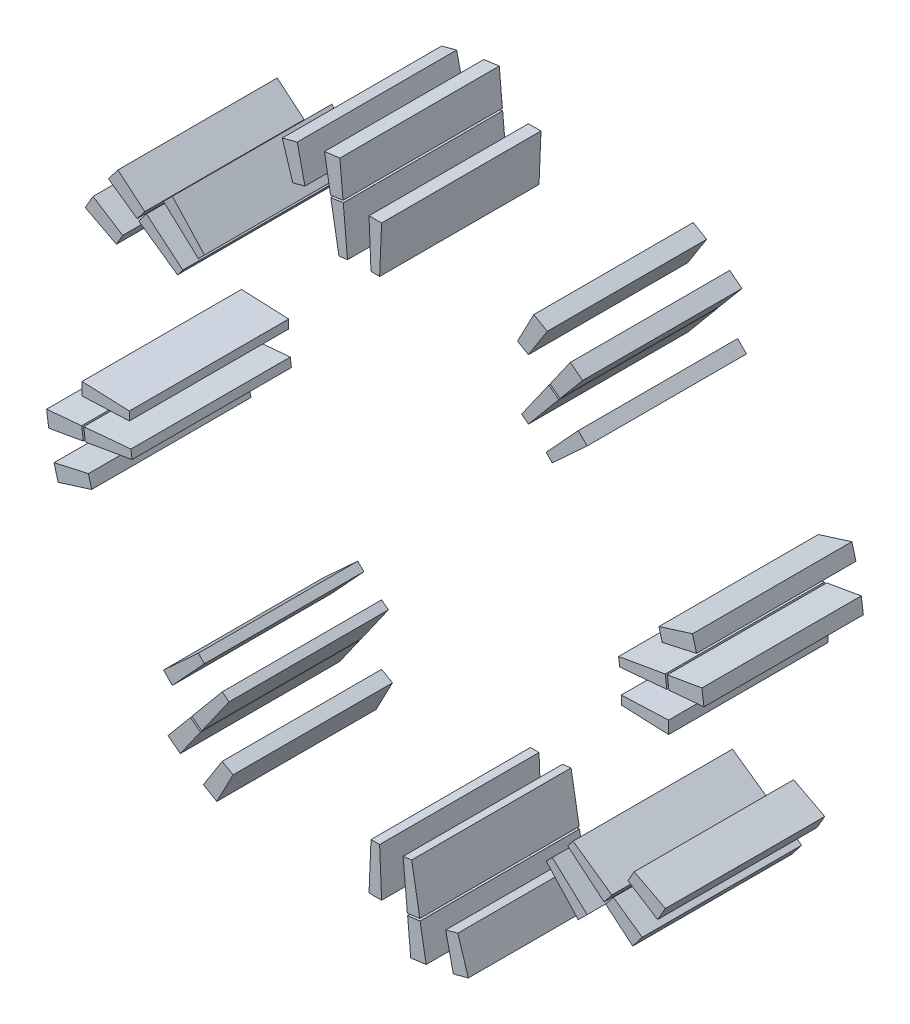
SolidWorks part; units mm, degrees
ref_plane "Спереди" through (0, 0, 0) normal (0, 0, 1) x (1, 0, 0)
ref_plane "Сверху" through (0, 0, 0) normal (0, 1, 0) x (1, 0, 0)
ref_plane "Справа" through (0, 0, 0) normal (1, 0, 0) x (0, 0, -1)
sketch "Эскиз1" plane through (0, 0, 0) normal (0, 0, 1) x (1, 0, 0)
  line L0 (46.2929, -0.8125) -> (55.2, -1.1828)
  line L1 (55.2, -1.1828) -> (55.2, 1.1828)
  line L2 (55.2, 1.1828) -> (46.2929, 0.8125)
  line L3 (46.2929, 0.8125) -> (46.2929, -0.8125)
  line L4 (55.2662, 6.0829) -> (61.8588, 6.6687)
  line L5 (61.8588, 6.6687) -> (61.477, 9.5687)
  line L6 (61.477, 9.5687) -> (54.9575, 8.4283)
  line L7 (54.9575, 8.4283) -> (55.2662, 6.0829)
  line L8 (46.0029, 5.2369) -> (54.8821, 6.0324)
  line L9 (54.8821, 6.0324) -> (54.5734, 8.3777)
  line L10 (54.5734, 8.3777) -> (45.7908, 6.848)
  line L11 (45.7908, 6.848) -> (46.0029, 5.2369)
  line L12 (53.9995, 13.2446) -> (60.4591, 14.6859)
  line L13 (60.4591, 14.6859) -> (59.7021, 17.5112)
  line L14 (59.7021, 17.5112) -> (53.3872, 15.5296)
  line L15 (53.3872, 15.5296) -> (53.9995, 13.2446)
  line L16 (33.3085, 32.1595) -> (39.8687, 38.1959)
  line L17 (39.8687, 38.1959) -> (38.1959, 39.8687)
  line L18 (38.1959, 39.8687) -> (32.1595, 33.3085)
  line L19 (32.1595, 33.3085) -> (33.3085, 32.1595)
  line L20 (34.7779, 43.3804) -> (39.0252, 48.4563)
  line L21 (39.0252, 48.4563) -> (36.7047, 50.2369)
  line L22 (36.7047, 50.2369) -> (32.9011, 44.8205)
  line L23 (32.9011, 44.8205) -> (34.7779, 43.3804)
  line L24 (28.8259, 36.232) -> (34.542, 43.0731)
  line L25 (34.542, 43.0731) -> (32.6653, 44.5131)
  line L26 (32.6653, 44.5131) -> (27.5367, 37.2212)
  line L27 (27.5367, 37.2212) -> (28.8259, 36.232)
  line L28 (28.818, 47.5487) -> (32.3666, 53.1355)
  line L29 (32.3666, 53.1355) -> (29.8334, 54.598)
  line L30 (29.8334, 54.598) -> (26.7694, 48.7315)
  line L31 (26.7694, 48.7315) -> (28.818, 47.5487)
  line L32 (0.8125, 46.2929) -> (1.1828, 55.2)
  line L33 (1.1828, 55.2) -> (-1.1828, 55.2)
  line L34 (-1.1828, 55.2) -> (-0.8125, 46.2929)
  line L35 (-0.8125, 46.2929) -> (0.8125, 46.2929)
  line L36 (-6.0829, 55.2662) -> (-6.6687, 61.8588)
  line L37 (-6.6687, 61.8588) -> (-9.5687, 61.477)
  line L38 (-9.5687, 61.477) -> (-8.4283, 54.9575)
  line L39 (-8.4283, 54.9575) -> (-6.0829, 55.2662)
  line L40 (-5.2369, 46.0029) -> (-6.0324, 54.8821)
  line L41 (-6.0324, 54.8821) -> (-8.3777, 54.5734)
  line L42 (-8.3777, 54.5734) -> (-6.848, 45.7908)
  line L43 (-6.848, 45.7908) -> (-5.2369, 46.0029)
  line L44 (-13.2446, 53.9995) -> (-14.6859, 60.4591)
  line L45 (-14.6859, 60.4591) -> (-17.5112, 59.7021)
  line L46 (-17.5112, 59.7021) -> (-15.5296, 53.3872)
  line L47 (-15.5296, 53.3872) -> (-13.2446, 53.9995)
  line L48 (-32.1595, 33.3085) -> (-38.1959, 39.8687)
  line L49 (-38.1959, 39.8687) -> (-39.8687, 38.1959)
  line L50 (-39.8687, 38.1959) -> (-33.3085, 32.1595)
  line L51 (-33.3085, 32.1595) -> (-32.1595, 33.3085)
  line L52 (-43.3804, 34.7779) -> (-48.4563, 39.0252)
  line L53 (-48.4563, 39.0252) -> (-50.2369, 36.7047)
  line L54 (-50.2369, 36.7047) -> (-44.8205, 32.9011)
  line L55 (-44.8205, 32.9011) -> (-43.3804, 34.7779)
  line L56 (-36.232, 28.8259) -> (-43.0731, 34.542)
  line L57 (-43.0731, 34.542) -> (-44.5131, 32.6653)
  line L58 (-44.5131, 32.6653) -> (-37.2212, 27.5367)
  line L59 (-37.2212, 27.5367) -> (-36.232, 28.8259)
  line L60 (-47.5487, 28.818) -> (-53.1355, 32.3666)
  line L61 (-53.1355, 32.3666) -> (-54.598, 29.8334)
  line L62 (-54.598, 29.8334) -> (-48.7315, 26.7694)
  line L63 (-48.7315, 26.7694) -> (-47.5487, 28.818)
  line L64 (-46.2929, 0.8125) -> (-55.2, 1.1828)
  line L65 (-55.2, 1.1828) -> (-55.2, -1.1828)
  line L66 (-55.2, -1.1828) -> (-46.2929, -0.8125)
  line L67 (-46.2929, -0.8125) -> (-46.2929, 0.8125)
  line L68 (-55.2662, -6.0829) -> (-61.8588, -6.6687)
  line L69 (-61.8588, -6.6687) -> (-61.477, -9.5687)
  line L70 (-61.477, -9.5687) -> (-54.9575, -8.4283)
  line L71 (-54.9575, -8.4283) -> (-55.2662, -6.0829)
  line L72 (-46.0029, -5.2369) -> (-54.8821, -6.0324)
  line L73 (-54.8821, -6.0324) -> (-54.5734, -8.3777)
  line L74 (-54.5734, -8.3777) -> (-45.7908, -6.848)
  line L75 (-45.7908, -6.848) -> (-46.0029, -5.2369)
  line L76 (-53.9995, -13.2446) -> (-60.4591, -14.6859)
  line L77 (-60.4591, -14.6859) -> (-59.7021, -17.5112)
  line L78 (-59.7021, -17.5112) -> (-53.3872, -15.5296)
  line L79 (-53.3872, -15.5296) -> (-53.9995, -13.2446)
  line L80 (-33.3085, -32.1595) -> (-39.8687, -38.1959)
  line L81 (-39.8687, -38.1959) -> (-38.1959, -39.8687)
  line L82 (-38.1959, -39.8687) -> (-32.1595, -33.3085)
  line L83 (-32.1595, -33.3085) -> (-33.3085, -32.1595)
  line L84 (-34.7779, -43.3804) -> (-39.0252, -48.4563)
  line L85 (-39.0252, -48.4563) -> (-36.7047, -50.2369)
  line L86 (-36.7047, -50.2369) -> (-32.9011, -44.8205)
  line L87 (-32.9011, -44.8205) -> (-34.7779, -43.3804)
  line L88 (-28.8259, -36.232) -> (-34.542, -43.0731)
  line L89 (-34.542, -43.0731) -> (-32.6653, -44.5131)
  line L90 (-32.6653, -44.5131) -> (-27.5367, -37.2212)
  line L91 (-27.5367, -37.2212) -> (-28.8259, -36.232)
  line L92 (-28.818, -47.5487) -> (-32.3666, -53.1355)
  line L93 (-32.3666, -53.1355) -> (-29.8334, -54.598)
  line L94 (-29.8334, -54.598) -> (-26.7694, -48.7315)
  line L95 (-26.7694, -48.7315) -> (-28.818, -47.5487)
  line L96 (-0.8125, -46.2929) -> (-1.1828, -55.2)
  line L97 (-1.1828, -55.2) -> (1.1828, -55.2)
  line L98 (1.1828, -55.2) -> (0.8125, -46.2929)
  line L99 (0.8125, -46.2929) -> (-0.8125, -46.2929)
  line L100 (6.0829, -55.2662) -> (6.6687, -61.8588)
  line L101 (6.6687, -61.8588) -> (9.5687, -61.477)
  line L102 (9.5687, -61.477) -> (8.4283, -54.9575)
  line L103 (8.4283, -54.9575) -> (6.0829, -55.2662)
  line L104 (5.2369, -46.0029) -> (6.0324, -54.8821)
  line L105 (6.0324, -54.8821) -> (8.3777, -54.5734)
  line L106 (8.3777, -54.5734) -> (6.848, -45.7908)
  line L107 (6.848, -45.7908) -> (5.2369, -46.0029)
  line L108 (13.2446, -53.9995) -> (14.6859, -60.4591)
  line L109 (14.6859, -60.4591) -> (17.5112, -59.7021)
  line L110 (17.5112, -59.7021) -> (15.5296, -53.3872)
  line L111 (15.5296, -53.3872) -> (13.2446, -53.9995)
  line L112 (32.1595, -33.3085) -> (38.1959, -39.8687)
  line L113 (38.1959, -39.8687) -> (39.8687, -38.1959)
  line L114 (39.8687, -38.1959) -> (33.3085, -32.1595)
  line L115 (33.3085, -32.1595) -> (32.1595, -33.3085)
  line L116 (43.3804, -34.7779) -> (48.4563, -39.0252)
  line L117 (48.4563, -39.0252) -> (50.2369, -36.7047)
  line L118 (50.2369, -36.7047) -> (44.8205, -32.9011)
  line L119 (44.8205, -32.9011) -> (43.3804, -34.7779)
  line L120 (36.232, -28.8259) -> (43.0731, -34.542)
  line L121 (43.0731, -34.542) -> (44.5131, -32.6653)
  line L122 (44.5131, -32.6653) -> (37.2212, -27.5367)
  line L123 (37.2212, -27.5367) -> (36.232, -28.8259)
  line L124 (47.5487, -28.818) -> (53.1355, -32.3666)
  line L125 (53.1355, -32.3666) -> (54.598, -29.8334)
  line L126 (54.598, -29.8334) -> (48.7315, -26.7694)
  line L127 (48.7315, -26.7694) -> (47.5487, -28.818)
extrude "Slot_copper_envelopes" add sketch "Эскиз1" along normal blind 30 from offset 15 separate body
